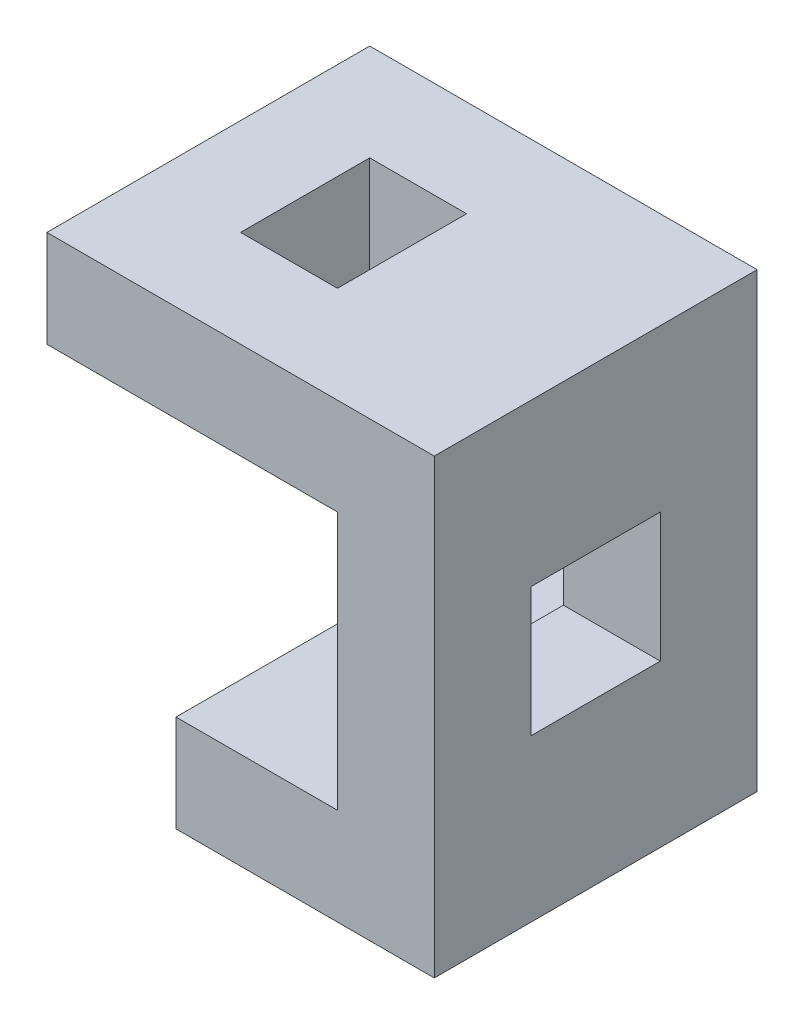
SolidWorks part; units mm, degrees
ref_plane "Front Plane" through (0, 0, 0) normal (0, 0, 1) x (1, 0, 0)
ref_plane "Top Plane" through (0, 0, 0) normal (0, 1, 0) x (1, 0, 0)
ref_plane "Right Plane" through (0, 0, 0) normal (1, 0, 0) x (0, 0, -1)
sketch "Sketch1" plane through (0, 0, 0) normal (0, 0, 1) x (1, 0, 0)
  line L0 (-60, 70) -> (0, 70)
  line L1 (0, 70) -> (0, 0)
  line L2 (0, 0) -> (-40, 0)
  line L3 (-40, 0) -> (-40, 15)
  line L4 (-40, 15) -> (-15, 15)
  line L5 (-15, 15) -> (-15, 55)
  line L6 (-15, 55) -> (-60, 55)
  line L9 (-60, 70) -> (-60, 55)
  point P8 (0, 0)
  dimension "D1" = 15
  dimension "D2" = 60
  dimension "D3" = 15
  dimension "D4" = 40
  dimension "D5" = 70
  dimension "D6" = 15
extrude "Boss-Extrude1" add sketch "Sketch1" along normal blind 50
sketch "Sketch2" plane through (0, 0, 0) normal (1, 0, 0) x (0, 0, -1)
  line L0 (-50, 0) -> (-50, 70) construction
  line L1 (-15, 45) -> (-35, 45)
  line L2 (-15, 45) -> (-15, 25)
  line L3 (-15, 25) -> (-35, 25)
  line L4 (-35, 45) -> (-35, 25)
  dimension "D1" = 20
  dimension "D2" = 20
  dimension "D3" = 15
  dimension "D4" = 25
extrude "Cut-Extrude1" cut sketch "Sketch2" against normal blind 50 contours L2 L1 L4 L3
sketch "Sketch4" plane through (0, 0, 0) normal (1, 0, 0) x (0, 0, -1)
sketch "ketch5" plane through (0, 0, 0) normal (1, 0, 0) x (0, 0, -1)
  point P8 (0, 0)
sketch "Sketch6" plane through (0, 70, 0) normal (0, 1, 0) x (1, 0, 0)
  line L0 (0, 0) -> (-60, 0) construction
  line L1 (-45, -15) -> (-30, -15)
  line L2 (-45, -15) -> (-45, -35)
  line L3 (-45, -35) -> (-30, -35)
  line L4 (-30, -15) -> (-30, -35)
  line L5 (-60, -50) -> (-60, 0) construction
  point P8 (0, 0)
  point P9 (-60, 0)
  dimension "D1" = 15
  dimension "D2" = 20
  dimension "D3" = 15
  dimension "D4" = 15
extrude "Cut-Extrude2" cut sketch "Sketch6" against normal blind 50
